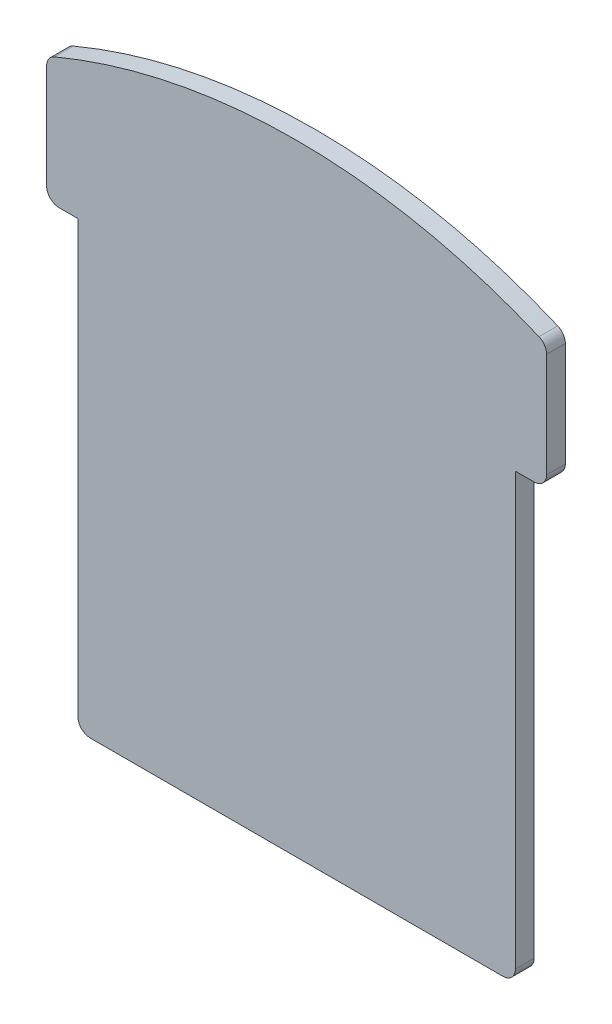
SolidWorks part; units mm, degrees
ref_plane "Plan de face" through (0, 0, 0) normal (0, 0, 1) x (1, 0, 0)
ref_plane "Plan de dessus" through (0, 0, 0) normal (0, 1, 0) x (1, 0, 0)
ref_plane "Plan de droite" through (0, 0, 0) normal (1, 0, 0) x (0, 0, -1)
sketch "Esquisse1" plane through (0, 0, 0) normal (0, 0, 1) x (1, 0, 0)
  line L1 (0, 0) -> (70, 0)
  line L2 (0, 0) -> (0, 71)
  line L3 (0, 71) -> (70, 71)
  line L4 (70, 0) -> (70, 71)
  dimension "D1" = 71
  dimension "D2" = 70
extrude "Boss.-Extru.1" add sketch "Esquisse1" along normal blind 3
sketch "Esquisse2" plane through (0, 0, 3) normal (0, 0, 1) x (1, 0, 0)
  line L0 (35, 71) -> (35, 91) construction
  line L1 (-5, 91) -> (75, 91) construction
  line L2 (-5, 91) -> (-5, 71)
  line L3 (-5, 71) -> (75, 71)
  line L4 (75, 91) -> (75, 71)
  line L5 (70, 71) -> (0, 71) construction
  arc A0 (-5, 91) -> (75, 91) centre (35, -0.6515) cw
  dimension "D3" = 100
  dimension "D1" = 20
  dimension "D2" = 80
extrude "Boss.-Extru.2" add sketch "Esquisse2" against normal up to vertex (3 mm away)
fillet "Congé1" radius 2 6 edges at (75, 71, 1.5) (-5, 71, 1.5) (70, 0, 1.5) (0, 0, 1.5) (75, 91, 1.5) (-5, 91, 1.5)
